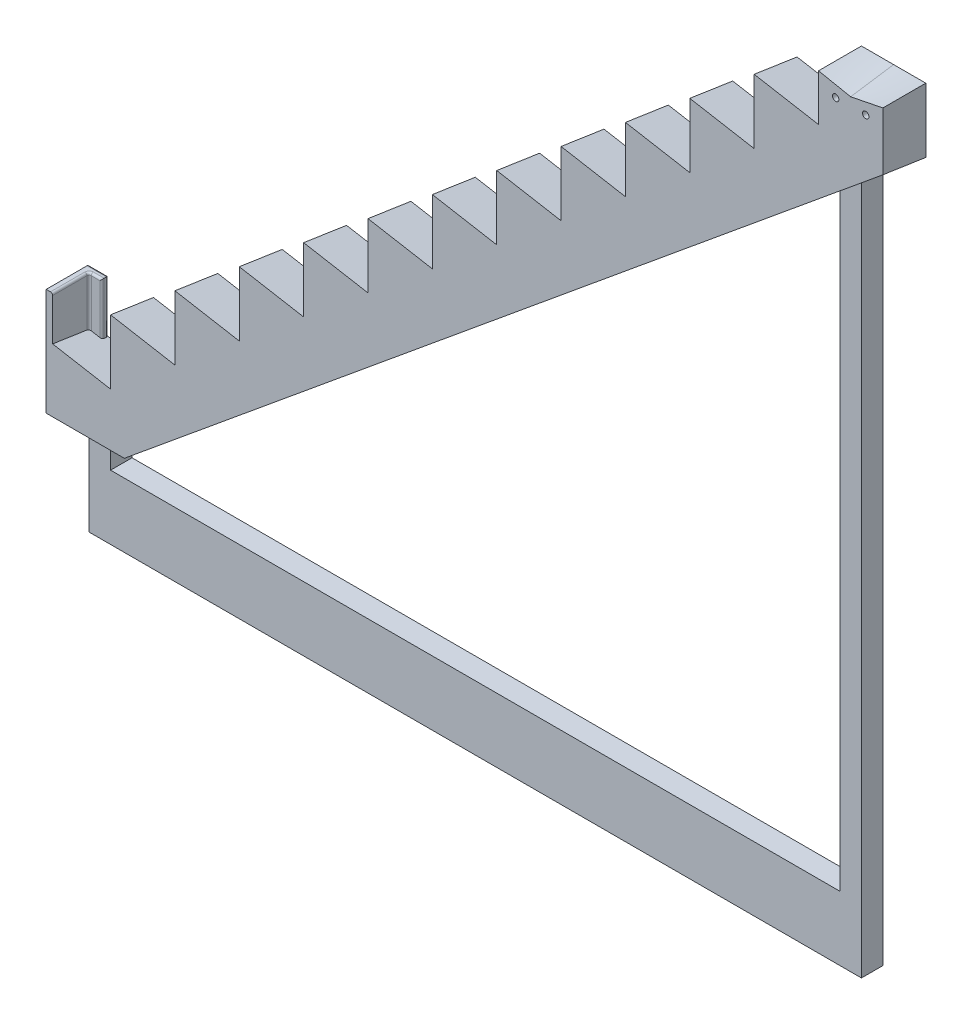
SolidWorks part; units mm, degrees
ref_plane "Front Plane" through (0, 0, 0) normal (0, 0, 1) x (1, 0, 0)
ref_plane "Top Plane" through (0, 0, 0) normal (0, 1, 0) x (1, 0, 0)
ref_plane "Right Plane" through (0, 0, 0) normal (1, 0, 0) x (0, 0, -1)
sketch "Sketch1" plane through (0, 0, 0) normal (0, 0, 1) x (1, 0, 0)
  line L0 (0, 0) -> (-30, 5.2898)
  line L1 (-30, 5.2898) -> (-30, -24.7102)
  line L2 (-30, -24.7102) -> (-60, -19.4204)
  line L3 (-60, -19.4204) -> (-60, -49.4204)
  line L4 (-60, -49.4204) -> (-90, -44.1306)
  line L5 (-90, -44.1306) -> (-90, -74.1306)
  line L6 (-90, -74.1306) -> (-120, -68.8408)
  line L7 (-120, -68.8408) -> (-120, -98.8408)
  line L8 (-120, -98.8408) -> (-150, -93.551)
  line L9 (-150, -93.551) -> (-150, -123.551)
  line L10 (-150, -123.551) -> (-180, -118.2611)
  line L11 (-180, -118.2611) -> (-180, -148.2611)
  line L12 (-180, -148.2611) -> (-210, -142.9713)
  line L13 (-210, -142.9713) -> (-210, -172.9713)
  line L14 (-210, -172.9713) -> (-240, -167.6815)
  line L15 (-240, -167.6815) -> (-240, -197.6815)
  line L16 (-240, -197.6815) -> (-270, -192.3917)
  line L17 (-270, -192.3917) -> (-270, -222.3917)
  line L18 (-270, -222.3917) -> (-300, -217.1019)
  line L19 (-300, -217.1019) -> (-300, -247.1019)
  line L20 (-300, -247.1019) -> (-330, -241.8121)
  line L21 (-330, -241.8121) -> (-330, -271.8121)
  line L22 (-330, -271.8121) -> (-360, -266.5223)
  line L23 (-360, -266.5223) -> (-360, -296.5223)
  line L24 (-360, -296.5223) -> (-390, -291.2325)
  line L25 (-390, -291.2325) -> (-390, -321.2325)
  line L26 (0, 0) -> (-390, -321.2325) construction
  line L27 (0, -30) -> (-353.5778, -321.2325)
  line L28 (0, -30) -> (0, 0)
  line L29 (-353.5778, -321.2325) -> (-390, -321.2325)
  dimension "D1" = 30
  dimension "D2" = 30
  dimension "D3" = 100
  dimension "D4" = 30
ref_plane "Plane1" through (0, 0, -20) normal (0, 0, 1) x (1, 0, 0)
sketch "Sketch2" plane through (0, 0, -20) normal (0, 0, 1) x (1, 0, 0)
  line L0 (0, 0) -> (-390, -321.2325) construction
  line L29 (-353.5778, -324.2325) -> (-390, -324.2325)
  line L30 (-390, -294.2325) -> (-390, -324.2325)
  line L31 (-360, -299.5223) -> (-390, -294.2325)
  line L32 (-360, -269.5223) -> (-360, -299.5223)
  line L33 (-330, -274.8121) -> (-360, -269.5223)
  line L34 (-330, -244.8121) -> (-330, -274.8121)
  line L35 (-300, -250.1019) -> (-330, -244.8121)
  line L36 (-300, -220.1019) -> (-300, -250.1019)
  line L37 (-270, -225.3917) -> (-300, -220.1019)
  line L38 (-270, -195.3917) -> (-270, -225.3917)
  line L39 (-240, -200.6815) -> (-270, -195.3917)
  line L40 (-240, -170.6815) -> (-240, -200.6815)
  line L41 (-210, -175.9713) -> (-240, -170.6815)
  line L42 (-210, -145.9713) -> (-210, -175.9713)
  line L43 (-180, -151.2611) -> (-210, -145.9713)
  line L44 (-180, -121.2611) -> (-180, -151.2611)
  line L45 (-150, -126.551) -> (-180, -121.2611)
  line L46 (-150, -96.551) -> (-150, -126.551)
  line L47 (-120, -101.8408) -> (-150, -96.551)
  line L48 (-120, -71.8408) -> (-120, -101.8408)
  line L49 (-90, -77.1306) -> (-120, -71.8408)
  line L50 (-90, -47.1306) -> (-90, -77.1306)
  line L51 (-60, -52.4204) -> (-90, -47.1306)
  line L52 (-60, -22.4204) -> (-60, -52.4204)
  line L53 (-30, -27.7102) -> (-60, -22.4204)
  line L54 (-30, 2.2898) -> (-30, -27.7102)
  line L55 (0, -3) -> (-30, 2.2898)
  line L56 (0, -33) -> (-353.5778, -324.2325)
  line L57 (0, -33) -> (0, -3)
  dimension "D1" = 30
  dimension "D2" = 30
  dimension "D3" = 100
  dimension "D4" = 30
  dimension "D5" = 3
loft "Loft1" add profiles "Sketch1", "Sketch2"
sketch "Sketch8" plane through (0, 0, -20) normal (0, 0, -1) x (-1, 0, 0)
  line L1 (0, -3) -> (30, -3)
  line L2 (0, -3) -> (0, 5.2898)
  line L3 (0, 5.2898) -> (30, 5.2898)
  line L4 (30, -3) -> (30, 5.2898)
sketch "Sketch7" plane through (0, 0, 0) normal (0, 0, 1) x (1, 0, 0)
  line L1 (0, 5.2898) -> (-30, 5.2898)
  line L2 (0, 5.2898) -> (0, -3)
  line L4 (-30, 5.2898) -> (-30, -3)
  line L5 (0, -3) -> (-30, -3) construction
  line L6 (-30, -3) -> (-15, -6)
  line L7 (-15, -6) -> (0, -3)
  point P4 (-15, -3)
  dimension "D1" = 3
loft "Cut-Loft1" cut profiles "Sketch8", "Sketch7"
ref_plane "Plane2" through (0, -291.2325, 0) normal (0, 1, 0) x (1, 0, 0)
sketch "Sketch9" plane through (0, -291.2325, 0) normal (0, 1, 0) x (1, 0, 0)
  line L0 (-390, 0) -> (-390, 20)
  line L1 (-181.2374, 20) -> (181.2374, 20) construction
  line L2 (-390, 0) -> (-390, 20) construction
  line L3 (-390, 20) -> (-381, 20)
  line L4 (-381, 20) -> (-381, 17)
  line L5 (-381, 17) -> (-387, 17)
  line L6 (-387, 17) -> (-387, 0)
  line L7 (-360, 0) -> (-390, 0) construction
  line L8 (-387, 0) -> (-390, 0)
  dimension "D1" = 9
  dimension "D2" = 3
  dimension "D3" = 3
extrude "Boss-Extrude3" add sketch "Sketch9" against normal blind 13 and the other way blind 20
fillet "Fillet2" radius 1 6 edges at (-387, -271.2325, -8.5) (-385.5, -271.2325, -20) (-384, -271.2325, -17) (-381, -283.3009, -17) (-387, -282.772, -17)
ref_plane "Plane3" through (0, -324.2325, 0) normal (0, 1, 0) x (1, 0, 0)
sketch "Sketch10" plane through (0, -324.2325, 0) normal (0, 1, 0) x (1, 0, 0)
  line L0 (-390, 0) -> (-353.5778, 0) construction
  line L1 (-375, 5) -> (-365, 5)
  line L2 (-375, 5) -> (-375, 15)
  line L3 (-375, 15) -> (-365, 15)
  line L4 (-365, 5) -> (-365, 15)
  line L7 (-390, 19) -> (-390, 0) construction
  dimension "D1" = 10
  dimension "D2" = 10
  dimension "D3" = 5
  dimension "D4" = 15
extrude "Boss-Extrude4" add sketch "Sketch10" against normal blind 40 and the other way blind 20 separate body
sketch "Sketch12" plane through (0, -324.2325, 0) normal (0, 1, 0) x (1, 0, 0)
  line L0 (0, 0) -> (0, 20) construction
  line L1 (-25, 5) -> (-15, 5)
  line L2 (-25, 5) -> (-25, 15)
  line L3 (-25, 15) -> (-15, 15)
  line L4 (-15, 5) -> (-15, 15)
  line L5 (-353.5778, 0) -> (0, 0) construction
  dimension "D1" = 15
  dimension "D2" = 5
  dimension "D3" = 10
  dimension "D4" = 10
extrude "Boss-Extrude5" add sketch "Sketch12" along normal blind 300 and the other way blind 40
sketch "Sketch13" plane through (0, 0, -15) normal (0, 0, -1) x (-1, 0, 0)
  line L0 (375, -304.2325) -> (375, -364.2325) construction
  line L1 (15, -364.2325) -> (375, -364.2325)
  line L2 (15, -364.2325) -> (15, -334.2325)
  line L3 (15, -334.2325) -> (375, -334.2325)
  line L4 (375, -364.2325) -> (375, -334.2325)
  dimension "D1" = 30
extrude "Boss-Extrude6" add sketch "Sketch13" against normal blind 10
sketch "Sketch14" plane through (0, 0, 0) normal (0, 0, 1) x (1, 0, 0)
  line L0 (-22, -9.8551) -> (-8, -9.8551) construction
  line L1 (-30, -13.8551) -> (0, -13.8551) construction
  line L2 (-30, -3) -> (-30, -24.7102) construction
  line L3 (0, -30) -> (0, -3) construction
  line L4 (-15, -21.6671) -> (-15, -6.0431) construction
  circle A0 centre (-22, -9.8551) radius 1.5
  circle A1 centre (-8, -9.8551) radius 1.5
  point P12 (-15, -13.8551)
  point P13 (-15, -9.8551)
  dimension "D1" = 3
  dimension "D2" = 4
  dimension "D3" = 14
extrude "Cut-Extrude1" cut sketch "Sketch14" against normal blind 10
